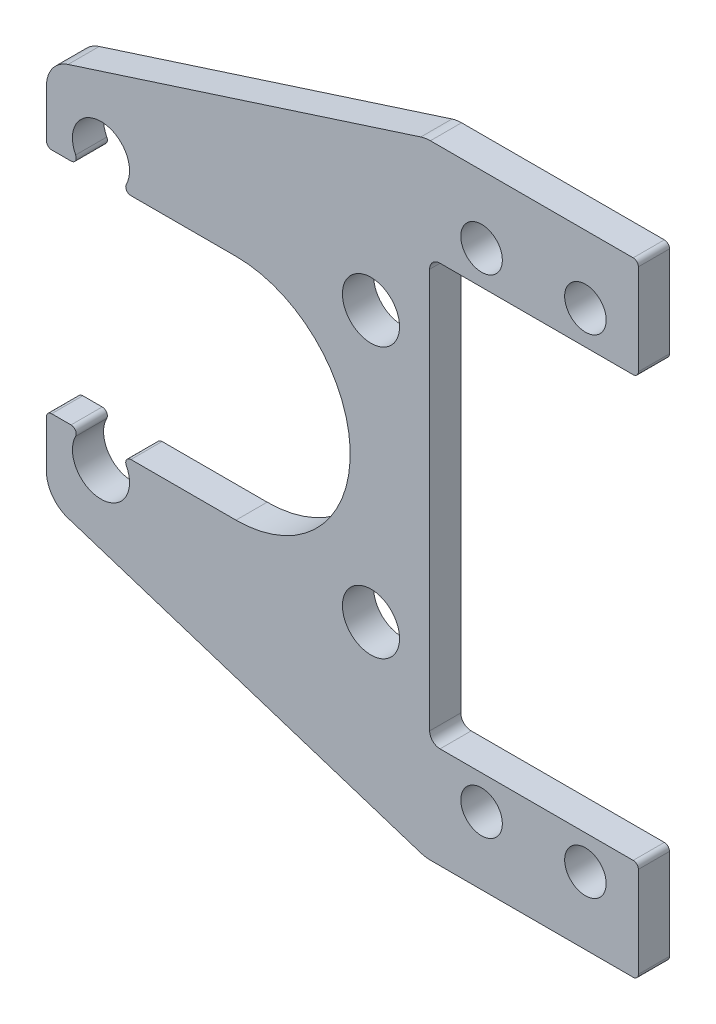
SolidWorks part; units mm, degrees
ref_plane "Front Plane" through (0, 0, 0) normal (1, 0, 0) x (0, 1, 0)
ref_plane "Top Plane" through (0, 0, 0) normal (0, 0, 1) x (0, 1, 0)
ref_plane "Right Plane" through (0, 0, 0) normal (0, 1, 0) x (-1, 0, 0)
sketch "Sketch1" plane through (0, 0, 0) normal (0, 0, 1) x (0, 1, 0)
  line L0 (0, 0) -> (0, -51.214) construction
  line L3 (-16.0641, 18.25) -> (-11.5, 18.25)
  line L5 (-18.25, -18.25) -> (7.7782, 7.7782) construction
  line L6 (-18.25, 18.25) -> (-11, 11) construction
  line L7 (-29.5, -38.75) -> (-20.75, -38.75)
  line L8 (-30, -38.25) -> (-30, -18.721)
  line L10 (30, -38.25) -> (30, -18.721)
  line L11 (-30, -38.75) -> (30, -18.25) construction
  line L12 (-20.25, -21.5812) -> (30, -38.75) construction
  line L14 (-20.25, -38.25) -> (-20.25, -19.65)
  line L15 (-19.25, -18.65) -> (19.25, -18.65)
  line L16 (20.25, -38.25) -> (20.25, -19.65)
  line L17 (-20.25, -38.75) -> (20.25, -18.65) construction
  line L18 (-20.25, -18.65) -> (20.25, -38.75) construction
  line L19 (20.75, -38.75) -> (29.5, -38.75)
  line L21 (-18.9198, 16.1693) -> (-29.8557, -17.8017)
  line L22 (18.9198, 16.1693) -> (29.8557, -17.8017)
  line L23 (0, 0) -> (-19.05, 0) construction
  line L24 (0, 0) -> (0, 15.5965) construction
  line L25 (-11, 0) -> (-11, 10.1169)
  line L26 (11, 0) -> (11, 10.1169)
  line L27 (11.5, 18.25) -> (16.0641, 18.25)
  line L28 (0, 0) -> (18.25, -18.25) construction
  line L29 (-11, 15.8831) -> (-11, 17.75)
  line L30 (11, 11) -> (18.25, 18.25) construction
  line L31 (11, 15.8831) -> (11, 17.75)
  arc A0 (19.25, -18.65) -> (20.25, -19.65) centre (19.25, -19.65) cw
  arc A1 (-20.25, -19.65) -> (-19.25, -18.65) centre (-19.25, -19.65) cw
  arc A2 (-11.7308, 15.4396) -> (-11.7308, 10.5604) centre (-13, 13) ccw
  arc A3 (-11, 0) -> (11, 0) centre (0, 0) ccw
  arc A4 (11.7308, 10.5604) -> (11.7308, 15.4396) centre (13, 13) ccw
  circle A5 centre (13, -13) radius 2.75
  circle A6 centre (-13, -13) radius 2.75
  circle A7 centre (-23.5, -23.65) radius 2
  circle A8 centre (23.5, -23.65) radius 2
  circle A9 centre (23.5, -33.65) radius 2
  circle A10 centre (-23.5, -33.65) radius 2
  arc A11 (11.7308, 15.4396) -> (11, 15.8831) centre (11.5, 15.8831) cw
  arc A12 (11.7308, 10.5604) -> (11, 10.1169) centre (11.5, 10.1169) ccw
  arc A13 (-11.7308, 10.5604) -> (-11, 10.1169) centre (-11.5, 10.1169) cw
  arc A14 (-11.7308, 15.4396) -> (-11, 15.8831) centre (-11.5, 15.8831) ccw
  arc A15 (-30, -18.721) -> (-29.8557, -17.8017) centre (-27, -18.721) cw
  arc A16 (29.8557, -17.8017) -> (30, -18.721) centre (27, -18.721) cw
  arc A17 (16.0641, 18.25) -> (18.9198, 16.1693) centre (16.0641, 15.25) cw
  arc A18 (-18.9198, 16.1693) -> (-16.0641, 18.25) centre (-16.0641, 15.25) cw
  arc A19 (-11.5, 18.25) -> (-11, 17.75) centre (-11.5, 17.75) cw
  arc A20 (11.5, 18.25) -> (11, 17.75) centre (11.5, 17.75) ccw
  arc A21 (-20.75, -38.75) -> (-20.25, -38.25) centre (-20.75, -38.25) ccw
  arc A22 (-29.5, -38.75) -> (-30, -38.25) centre (-29.5, -38.25) cw
  arc A23 (29.5, -38.75) -> (30, -38.25) centre (29.5, -38.25) ccw
  arc A24 (20.75, -38.75) -> (20.25, -38.25) centre (20.75, -38.25) cw
  point P0 (0, 0)
  point P6 (0, -28.5)
  point P11 (0, -28.7)
  point P47 (11, 14.8875)
  point P61 (-11, 14.8875)
  point P64 (-30, -18.25)
  point P76 (-11, 18.25)
  point P79 (11, 18.25)
  dimension "D7" = 1
  dimension "D9" = 5.5
  dimension "D12" = 22
  dimension "D15" = 4
  dimension "D20" = 0.5
  dimension "D21" = 3
  dimension "D22" = 0.5
  dimension "D23" = 0.5
  dimension "D1" = 36.5
  dimension "D2" = 36.5
  dimension "D3" = 9.75
  dimension "D4" = 20.5
  dimension "D5" = 40.5
  dimension "D6" = 20.1
  dimension "D8" = 9.75
  dimension "D10" = 13
  dimension "D11" = 13
  dimension "D16" = 3.25
  dimension "D19" = 5
  dimension "D13" = 2
  dimension "D14" = 2
  dimension "D17" = 2
  dimension "D18" = 2
extrude "Boss-Extrude1" add sketch "Sketch1" along normal blind 3
